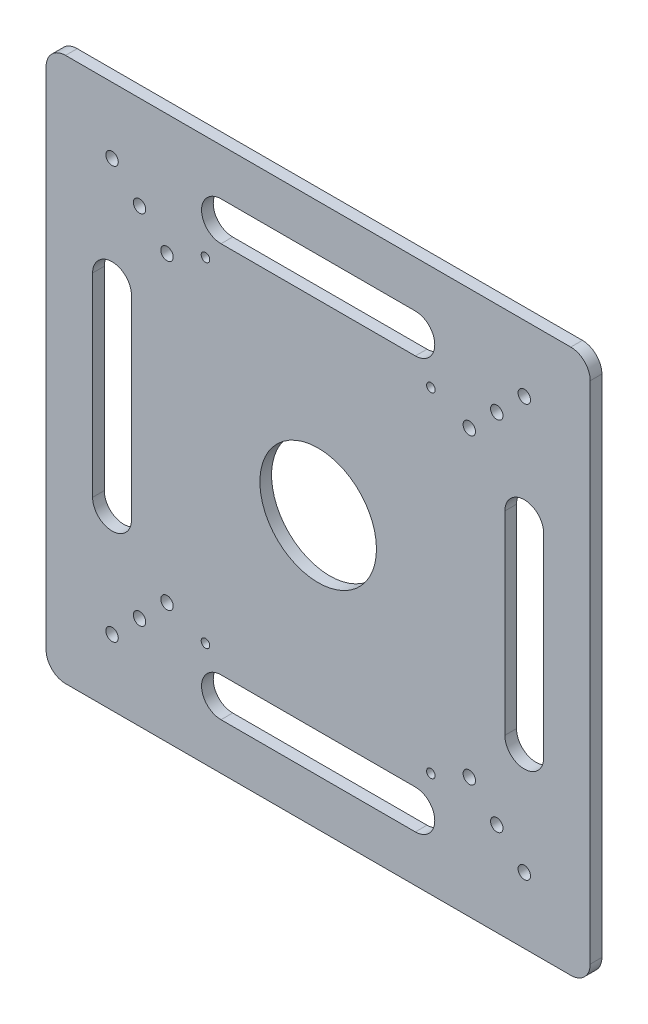
SolidWorks part; units mm, degrees
ref_plane "前视基准面" through (0, 0, 0) normal (0, 0, 1) x (1, 0, 0)
ref_plane "上视基准面" through (0, 0, 0) normal (0, 1, 0) x (1, 0, 0)
ref_plane "右视基准面" through (0, 0, 0) normal (1, 0, 0) x (0, 0, -1)
sketch "草图1" plane through (0, 0, 0) normal (0, 0, 1) x (1, 0, 0)
  line L0 (0, 0) -> (53.033, 53.033) construction
  line L1 (-70, 70) -> (70, 70)
  line L2 (-70, 70) -> (-70, -70)
  line L3 (70, 70) -> (70, -70)
  line L4 (-70, -70) -> (70, -70)
  line L5 (-70, 70) -> (70, -70) construction
  line L6 (70, 70) -> (-70, -70) construction
  line L7 (0, 0) -> (0, 53.033) construction
  line L8 (-25, 53.033) -> (25, 53.033) construction
  line L9 (-29, 43) -> (29, 43) construction
  line L10 (-25, 58.033) -> (25, 58.033)
  line L11 (-25, 48.033) -> (25, 48.033)
  line L12 (-29, 43) -> (-29, -43) construction
  line L13 (29, 43) -> (29, -43) construction
  line L14 (-29, -43) -> (29, -43) construction
  line L15 (-29, 43) -> (29, -43) construction
  line L16 (29, 43) -> (-29, -43) construction
  line L17 (-70, 0) -> (70, 0) construction
  line L18 (53.033, 25) -> (53.033, -25) construction
  line L19 (58.033, 25) -> (58.033, -25)
  line L20 (48.033, 25) -> (48.033, -25)
  line L21 (25, -53.033) -> (-25, -53.033) construction
  line L22 (25, -58.033) -> (-25, -58.033)
  line L23 (25, -48.033) -> (-25, -48.033)
  line L24 (-53.033, -25) -> (-53.033, 25) construction
  line L25 (-58.033, -25) -> (-58.033, 25)
  line L26 (-48.033, -25) -> (-48.033, 25)
  circle A0 centre (53.033, 53.033) radius 1.6
  arc A1 (-25, 58.033) -> (-25, 48.033) centre (-25, 53.033) ccw
  arc A2 (25, 48.033) -> (25, 58.033) centre (25, 53.033) ccw
  circle A3 centre (-29, 43) radius 1.1
  circle A4 centre (29, 43) radius 1.1
  circle A5 centre (29, -43) radius 1.1
  circle A6 centre (-29, -43) radius 1.1
  circle A7 centre (53.033, -53.033) radius 1.6
  arc A8 (58.033, 25) -> (48.033, 25) centre (53.033, 25) ccw
  arc A9 (48.033, -25) -> (58.033, -25) centre (53.033, -25) ccw
  circle A10 centre (-53.033, -53.033) radius 1.6
  arc A11 (25, -58.033) -> (25, -48.033) centre (25, -53.033) ccw
  arc A12 (-25, -48.033) -> (-25, -58.033) centre (-25, -53.033) ccw
  circle A13 centre (-53.033, 53.033) radius 1.6
  arc A14 (-58.033, -25) -> (-48.033, -25) centre (-53.033, -25) ccw
  arc A15 (-48.033, 25) -> (-58.033, 25) centre (-53.033, 25) ccw
  circle A16 centre (45.9619, 45.9619) radius 1.6
  circle A17 centre (38.8909, 38.8909) radius 1.6
  circle A18 centre (45.9619, -45.9619) radius 1.6
  circle A19 centre (38.8909, -38.8909) radius 1.6
  circle A20 centre (-45.9619, -45.9619) radius 1.6
  circle A21 centre (-38.8909, -38.8909) radius 1.6
  circle A22 centre (-45.9619, 45.9619) radius 1.6
  circle A23 centre (-38.8909, 38.8909) radius 1.6
  circle A24 centre (0, 0) radius 15
  point P10 (0, 53.033)
  point P22 (0, 0)
  point P35 (53.033, 0)
  point P44 (0, -53.033)
  point P53 (-53.033, 0)
  point P58 (0, 0)
  point P75 (0, 0)
  dimension "D2" = 3.2
  dimension "D5" = 58
  dimension "D7" = 2.2
  dimension "D8" = 2.2
  dimension "D12" = 30
  dimension "D1" = 75
  dimension "D3" = 140
  dimension "D4" = 140
  dimension "D6" = 86
  dimension "D9" = 4
  dimension "D11" = 4
  dimension "D10" = 3
extrude "凸台-拉伸1" add sketch "草图1" along normal blind 3
fillet "圆角1" radius 5 4 edges at (70, -70, 1.5) (-70, -70, 1.5) (-70, 70, 1.5) (70, 70, 1.5)
